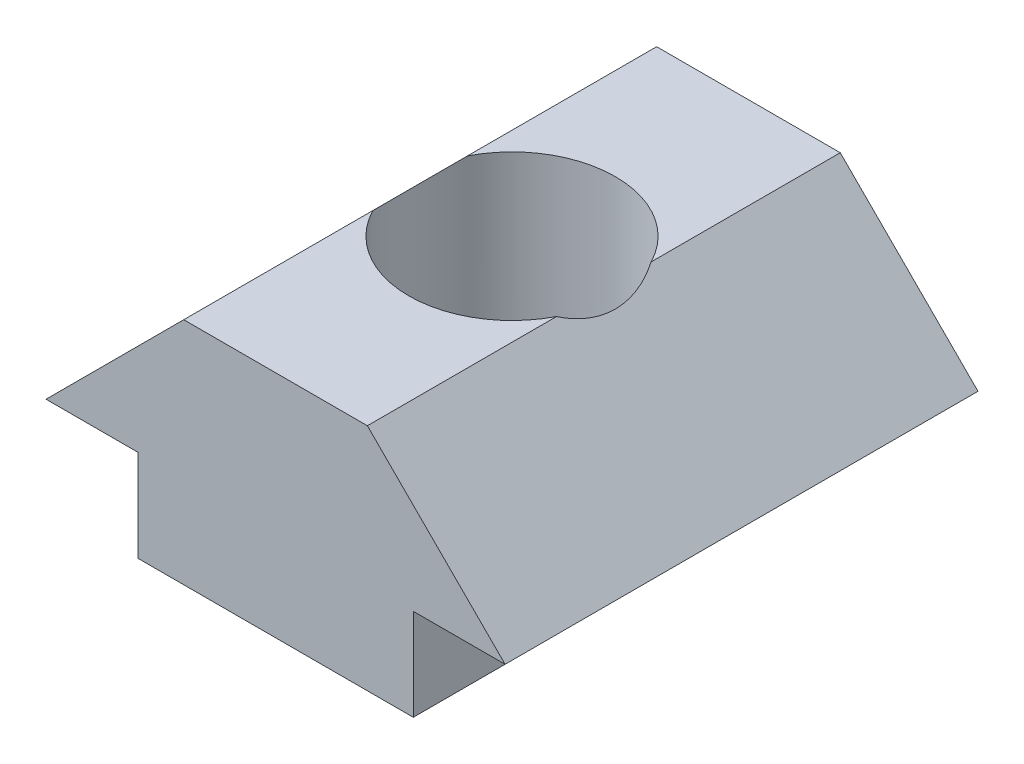
SolidWorks part; units mm, degrees
ref_plane "Plan de face" through (0, 0, 0) normal (0, 0, 1) x (1, 0, 0)
ref_plane "Plan de dessus" through (0, 0, 0) normal (0, 1, 0) x (1, 0, 0)
ref_plane "Plan de droite" through (0, 0, 0) normal (1, 0, 0) x (0, 0, -1)
sketch "Esquisse1" plane through (0, 0, 0) normal (0, 0, 1) x (1, 0, 0)
  line L0 (0, 0) -> (0, 2)
  line L1 (0, 2) -> (2, 2)
  line L2 (2, 2) -> (-1, 5)
  line L3 (-1, 5) -> (-5, 5)
  line L4 (-5, 5) -> (-8, 2)
  line L5 (-8, 2) -> (-6, 2)
  line L6 (-6, 2) -> (-6, 0)
  line L7 (-6, 0) -> (0, 0)
  point P11 (-3, 5)
  point P12 (-3, 0)
  dimension "D1" = 5
  dimension "D2" = 10
  dimension "D3" = 6
  dimension "D4" = 4
  dimension "D5" = 2
extrude "Boss.-Extru.1" add sketch "Esquisse1" along normal blind 10.3
hole_wizard "Dégagement M41" positions "Esquisse2" profile "Esquisse3" hole size "M4" standard "ISO" end condition through all
sketch "Esquisse2" plane through (0, 5, 0) normal (0, 1, 0) x (1, 0, 0)
  line L0 (-3, 0) -> (-3, -10.3) construction
  line L1 (-1, 0) -> (-5, 0) construction
  line L2 (-1, -10.3) -> (-5, -10.3) construction
  line L4 (-5, -5.15) -> (-1, -5.15) construction
  line L5 (-5, -10.3) -> (-5, 0) construction
  line L6 (-1, -10.3) -> (-1, 0) construction
  point P0 (-3, -5.15)
sketch "Esquisse3" plane through (-3, 5, 5.15) normal (1, 0, 0) x (0, 0, 1)
  line L0 (0, 0) -> (0, 5)
  line L1 (0, 5) -> (2.25, 5)
  line L2 (2.25, 5) -> (2.25, 0)
  line L5 (2.25, 0) -> (0, 0)
  line L11 (0, -6.35) -> (0, 107.95) construction
  dimension "Diamètre du perçage jusqu'au prochain" = 4.5
  dimension "Profondeur du perçage jusqu'au prochain" = 5
